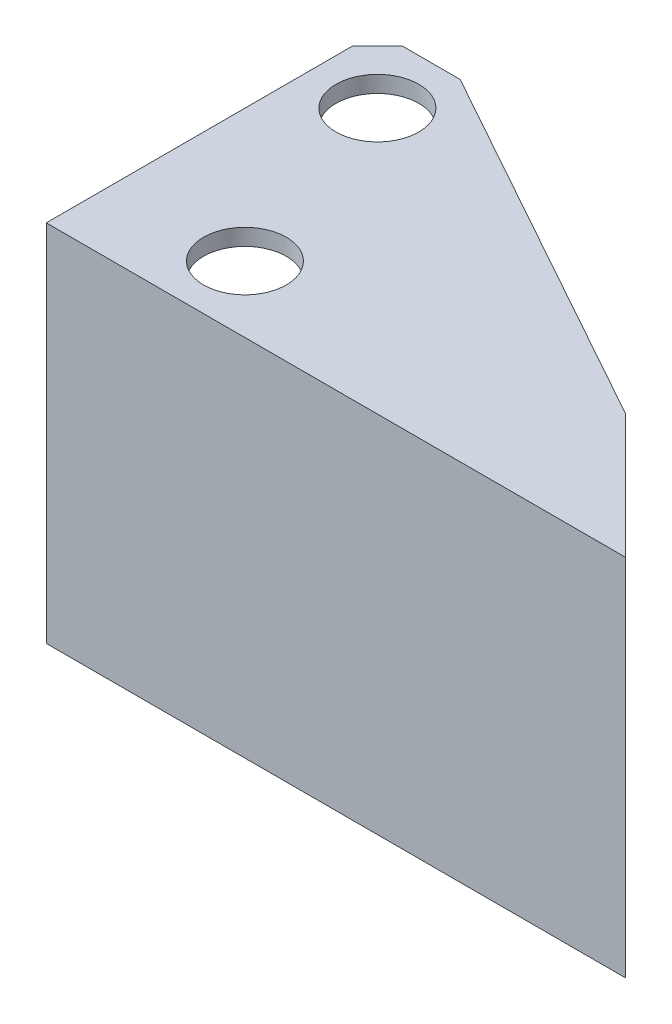
SolidWorks part; units mm, degrees
ref_plane "Front Plane" through (0, 0, 0) normal (0, 0, 1) x (1, 0, 0)
ref_plane "Top Plane" through (0, 0, 0) normal (0, 1, 0) x (1, 0, 0)
ref_plane "Right Plane" through (0, 0, 0) normal (1, 0, 0) x (0, 0, -1)
sketch "Sketch4" plane through (0, 0, 0) normal (0, 1, 0) x (1, 0, 0)
  line L1 (0, 0) -> (70, 0)
  line L2 (0, 0) -> (0, 40)
  line L3 (0, 40) -> (70, 40)
  line L4 (70, 0) -> (70, 40)
extrude "Boss-Extrude3" add sketch "Sketch4" along normal blind 44
sketch "Sketch5" plane through (0, 0, 0) normal (-1, 0, 0) x (0, 0, 1)
  line L0 (-40, 44) -> (-40, 0) construction
  line L1 (-2, 2) -> (-40, 2)
  line L2 (-2, 2) -> (-2, 42)
  line L3 (-2, 42) -> (-40, 42)
  line L4 (-40, 2) -> (-40, 42)
extrude "Cut-Extrude5" cut sketch "Sketch5" against normal through all
sketch "Sketch8" plane through (0, 44, 0) normal (0, 1, 0) x (1, 0, 0)
  line L0 (0, 0) -> (70, 0) construction
  line L2 (70, 0) -> (70, 40) construction
  line L3 (70, 40) -> (0, 40) construction
  line L4 (0, 40) -> (0, 0) construction
  line L5 (10, 40) -> (55, 15)
  line L6 (55, 15) -> (70, 0)
  line L7 (70, 0) -> (70, 40)
  line L8 (70, 40) -> (10, 40)
  point P0 (55, 15)
  point P5 (10, 40)
  dimension "D1" = 15
  dimension "D2" = 15
  dimension "D3" = 10
extrude "Cut-Extrude8" cut sketch "Sketch8" against normal through all
chamfer "Chamfer2" distance 3 angle 45 2 edges at (0, 1, -40) (0, 43, -40)
sketch "Sketch9" plane through (0, 44, 0) normal (0, 1, 0) x (1, 0, 0)
  line L0 (0, 37) -> (0, 0) construction
  line L1 (10, 40) -> (3, 40) construction
  line L2 (0, 0) -> (70, 0) construction
  circle A0 centre (8, 32) radius 5
  circle A1 centre (16, 8) radius 5
  dimension "D3" = 8
  dimension "D1" = 8
  dimension "D2" = 8
  dimension "D4" = 16
extrude "Cut-Extrude9" cut sketch "Sketch9" against normal through all
